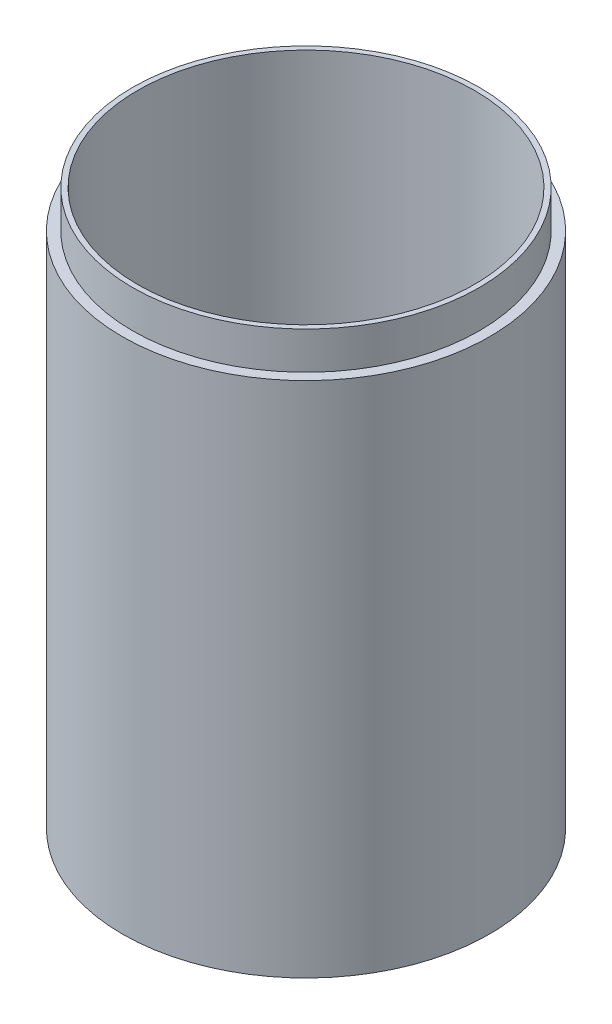
SolidWorks part; units mm, degrees
material "6061 Alloy"
ref_plane "Front Plane" through (0, 0, 0) normal (0, 0, 1) x (1, 0, 0)
ref_plane "Top Plane" through (0, 0, 0) normal (0, 1, 0) x (1, 0, 0)
ref_plane "Right Plane" through (0, 0, 0) normal (1, 0, 0) x (0, 0, -1)
sketch "Sketch1" plane through (0, 0, 0) normal (0, 0, 1) x (1, 0, 0)
  line L0 (22.86, 0) -> (22.86, -64.4207)
  line L1 (22.86, -64.4207) -> (0, -64.4207)
  line L2 (0, -64.4207) -> (0, -62.8968)
  line L3 (0, -62.8968) -> (20.955, -62.8968)
  line L4 (20.955, -62.8968) -> (20.955, 4.6672)
  line L5 (20.955, 4.6672) -> (22.225, 4.6672)
  line L6 (22.225, 4.6672) -> (22.225, 2.286)
  line L7 (22.225, 2.286) -> (21.59, 2.286)
  line L8 (21.59, 2.286) -> (21.59, 0)
  line L9 (21.59, 0) -> (22.225, 0)
  line L10 (22.225, 0) -> (22.86, 0)
  line L11 (20.955, 4.6672) -> (0, 4.6672) construction
  line L12 (0, 3.1432) -> (20.955, 3.1432) construction
  line L13 (20.955, 0.6032) -> (0, 0.6032) construction
  line L14 (20.955, -60.3567) -> (0, -60.3567) construction
  line L15 (0, 33.2677) -> (0, -75.4715) construction
  dimension "D1" = 22.86
  dimension "D2" = 0.635
  dimension "D3" = 1.905
  dimension "D4" = 1.524
  dimension "D5" = 0.635
  dimension "D6" = 2.286
  dimension "D7" = 0.635
  dimension "D8" = 2.3813
  dimension "D9" = 20.955
  dimension "D10" = 1.524
  dimension "D11" = 2.54
  dimension "D12" = 2.54
  dimension "D13" = 60.96
revolve "Revolve1" add sketch "Sketch1" angle 360 about L15
sketch "Sketch2" plane through (0, 4.6672, 0) normal (0, 1, 0) x (1, 0, 0)
  circle A0 centre (0, 0) radius 22.225
  circle A1 centre (0, 0) radius 22.225 construction
  circle A2 centre (0, 0) radius 21.59
  circle A3 centre (0, 0) radius 21.59 construction
extrude "Cut-Extrude1" cut sketch "Sketch2" against normal up to next
